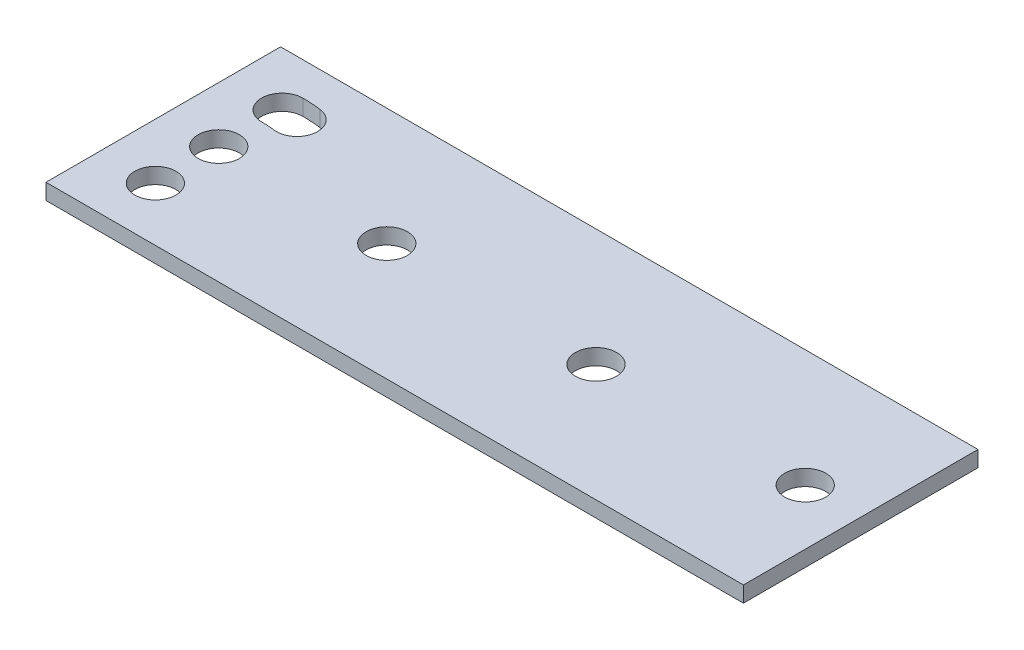
SolidWorks part; units mm, degrees
material "1.0553 (S355J0)"
ref_plane "Płaszczyzna przednia" through (0, 0, 0) normal (0, 0, 1) x (1, 0, 0)
ref_plane "Płaszczyzna górna" through (0, 0, 0) normal (0, 1, 0) x (1, 0, 0)
ref_plane "Płaszczyzna prawa" through (0, 0, 0) normal (1, 0, 0) x (0, 0, -1)
sketch "Szkic1" plane through (0, 0, 0) normal (0, 1, 0) x (1, 0, 0)
  line L0 (0, 37) -> (220, 37) construction
  line L1 (0, 0) -> (220, 0)
  line L2 (0, 0) -> (0, 74)
  line L3 (0, 74) -> (220, 74)
  line L4 (220, 0) -> (220, 74)
  line L5 (110, 74) -> (110, 0) construction
  circle A0 centre (17.5, 37) radius 6.5
  circle A1 centre (70.5, 37) radius 6.5
  circle A2 centre (202.5, 37) radius 6.5
  circle A3 centre (136.5, 37) radius 6.5
  circle A4 centre (17.5, 17) radius 6.5
  arc A5 (17.5, 63.5) -> (17.5, 50.5) centre (17.5, 57) ccw
  circle A6 centre (17.5, 17) radius 40 construction
  arc A7 (21.6875, 50.2373) -> (23.3125, 63.1353) centre (22.5, 56.6863) ccw
  arc A8 (21.6875, 50.2373) -> (17.5, 50.5) centre (17.5, 17) ccw
  arc A9 (23.3125, 63.1353) -> (17.5, 63.5) centre (17.5, 17) ccw
  dimension "D4" = 13
  dimension "D5" = 13
  dimension "D1" = 220
  dimension "D2" = 74
  dimension "D3" = 92.5
  dimension "D6" = 39.5
  dimension "D7" = 40
  dimension "D8" = 20
  dimension "D9" = 5
  dimension "D10" = 66
extrude "Dodanie-wyciągnięcie1" add sketch "Szkic1" along normal blind 5
